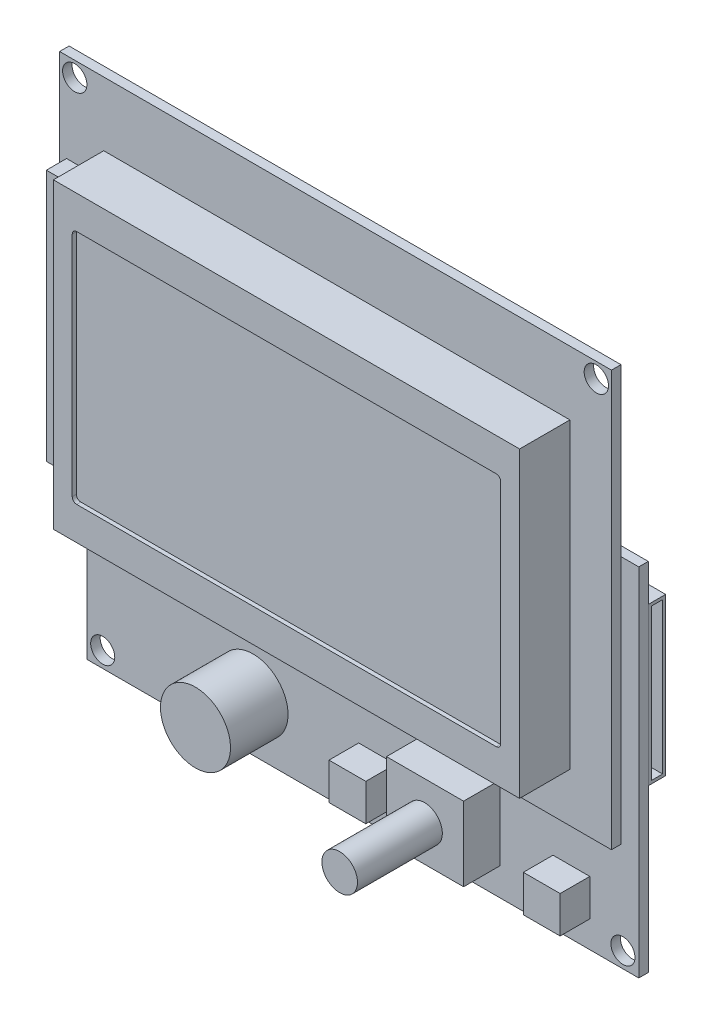
SolidWorks part; units mm, degrees
ref_plane "Front Plane" through (0, 0, 0) normal (0, 0, 1) x (1, 0, 0)
ref_plane "Top Plane" through (0, 0, 0) normal (0, 1, 0) x (1, 0, 0)
ref_plane "Right Plane" through (0, 0, 0) normal (1, 0, 0) x (0, 0, -1)
ref_plane "Plane2" through (0, 0, 4.6) normal (0, 0, -1) x (-1, 0, 0)
sketch "Sketch6" plane through (0, 0, 4.6) normal (0, 0, -1) x (-1, 0, 0)
  line L0 (4.6, 88.466) -> (0.5, 88.466) construction
  line L24 (0, 21.016) -> (93, 21.016)
  line L25 (93, 21.016) -> (93, 91.016)
  line L26 (93, 91.016) -> (0, 91.016)
  line L27 (0, 91.016) -> (0, 21.016)
  line L28 (0, 0) -> (-20.1226, 0) construction
  line L29 (92.5, 88.466) -> (88.4, 88.466) construction
  circle A0 centre (90.45, 88.466) radius 2.05
  circle A1 centre (2.55, 88.466) radius 2.05
extrude "Green PCB" add sketch "Sketch6" against normal blind 1.6 separate body
ref_plane "Plane6" through (0, 0, 1.6) normal (0, 0, 1) x (1, 0, 0)
sketch "Sketch57" plane through (0, 0, 1.6) normal (0, 0, 1) x (1, 0, 0)
  line L0 (-93, 60) -> (-93, 0)
  line L1 (-93, 0) -> (0, 0)
  line L2 (0, 0) -> (0, 60)
  line L3 (0, 60) -> (-93, 60)
  line L4 (0, 0) -> (25.8549, 0) construction
  circle A0 centre (-2.667, 2.667) radius 2.032
  circle A1 centre (-90.333, 2.667) radius 2.032
extrude "White PCB" add sketch "Sketch57" against normal blind 1.6 separate body
sketch "Sketch122" plane through (0, 0, 0) normal (0, 0, 1) x (1, 0, 0)
  line L2 (-84.11, 60) -> (-84.11, 0)
  line L3 (-84.11, 41.966) -> (-84.11, 39.934)
  line L4 (-76.49, 41.966) -> (-76.49, 39.934)
  line L5 (0, 39.68) -> (-93, 39.68)
  line L6 (-76.744, 39.68) -> (-83.856, 39.68)
  line L7 (-76.744, 42.22) -> (-83.856, 42.22)
  line L8 (0, 42.22) -> (-93, 42.22) construction
  line L9 (-84.11, 60) -> (-84.11, 0) construction
  line L10 (0, 39.68) -> (-93, 39.68) construction
  line L11 (-76.49, 60) -> (-76.49, 0) construction
  arc A0 (-83.856, 42.22) -> (-84.11, 41.966) centre (-83.856, 41.966) ccw
  arc A1 (-84.11, 39.934) -> (-83.856, 39.68) centre (-83.856, 39.934) ccw
  arc A2 (-76.744, 39.68) -> (-76.49, 39.934) centre (-76.744, 39.934) ccw
  arc A3 (-76.49, 41.966) -> (-76.744, 42.22) centre (-76.744, 41.966) ccw
  dimension "D3" = 0.254
  dimension "D1" = 8.89
  dimension "D2" = 20.32
extrude "Jumper" add sketch "Sketch122" against normal blind 8.509
sketch "Sketch123" plane through (0, 0, 4.6) normal (0, 0, -1) x (-1, 0, 0)
  line L2 (80.3, 21.016) -> (80.3, 91.016)
  line L3 (80.3, 21.905) -> (80.3, 22.921)
  line L8 (29.718, 23.175) -> (80.046, 23.175)
  line L9 (0, 21.651) -> (93, 21.651)
  line L10 (29.718, 21.651) -> (80.046, 21.651)
  line L12 (0, 23.175) -> (93, 23.175) construction
  line L13 (29.464, 91.016) -> (29.464, 21.016)
  line L14 (29.464, 22.921) -> (29.464, 21.905)
  line L15 (0, 21.651) -> (93, 21.651) construction
  arc A0 (29.718, 23.175) -> (29.464, 22.921) centre (29.718, 22.921) ccw
  arc A1 (29.464, 21.905) -> (29.718, 21.651) centre (29.718, 21.905) ccw
  arc A2 (80.046, 23.175) -> (80.3, 22.921) centre (80.046, 22.921) cw
  arc A3 (80.3, 21.905) -> (80.046, 21.651) centre (80.046, 21.905) cw
  dimension "D4" = 0.254
  dimension "D1" = 12.7
  dimension "D2" = 0.635
  dimension "D3" = 29.464
extrude "LCD Pins" add sketch "Sketch123" along normal up to surface (3 mm away) up to face at (-88.301, 2.667, 1.6)
ref_plane "Plane8" through (0, 0, 6.2) normal (0, 0, 1) x (1, 0, 0)
sketch "Sketch98" plane through (0, 0, 6.2) normal (0, 0, 1) x (1, 0, 0)
  line L0 (-85.56, 75.98) -> (-91.83, 75.98)
  line L1 (-91.83, 75.98) -> (-91.83, 33.48)
  line L2 (-91.83, 33.48) -> (-85.56, 33.48)
  line L3 (-85.56, 33.48) -> (-85.56, 29.25)
  line L4 (-85.56, 29.25) -> (-7, 29.25)
  line L5 (-7, 29.25) -> (-7, 80.25)
  line L6 (-7, 80.25) -> (-85.56, 80.25)
  line L7 (-85.56, 80.25) -> (-85.56, 75.98)
extrude "LCD Base" add sketch "Sketch98" along normal blind 3.4
ref_plane "Plane9" through (0, 0, 9.5999) normal (0, 0, 1) x (1, 0, 0)
sketch "Sketch109" plane through (0, 0, 9.5999) normal (0, 0, 1) x (1, 0, 0)
  line L0 (-85.56, 29.25) -> (-85.56, 80.25)
  line L1 (-85.56, 29.25) -> (-7, 29.25)
  line L2 (-7, 29.25) -> (-7, 80.25)
  line L3 (-85.56, 80.25) -> (-7, 80.25)
extrude "LCD Screen" add sketch "Sketch109" along normal blind 5.0836
ref_plane "Plane10" through (0, 0, 14.7521) normal (0, 0, 1) x (1, 0, 0)
sketch "Sketch121" plane through (0, 0, 14.7521) normal (0, 0, 1) x (1, 0, 0)
  line L0 (-82.385, 73.9) -> (-82.385, 35.6)
  line L1 (-10.175, 35.6) -> (-10.175, 73.9)
  line L2 (-81.623, 74.662) -> (-10.937, 74.662)
  line L3 (-81.623, 34.838) -> (-10.937, 34.838)
  arc A0 (-82.385, 35.6) -> (-81.623, 34.838) centre (-81.623, 35.6) ccw
  arc A1 (-10.937, 34.838) -> (-10.175, 35.6) centre (-10.937, 35.6) ccw
  arc A2 (-10.175, 73.9) -> (-10.937, 74.662) centre (-10.937, 73.9) ccw
  arc A3 (-81.623, 74.662) -> (-82.385, 73.9) centre (-81.623, 73.9) ccw
extrude "LCD Glass" cut sketch "Sketch121" against normal blind 0.762
ref_plane "Plane4" through (0, 0, -2.93) normal (0, 0, -1) x (-1, 0, 0)
sketch "Sketch17" plane through (0, 0, -2.93) normal (0, 0, -1) x (-1, 0, 0)
  line L0 (25.5, 53.721) -> (0, 53.721)
  line L1 (0, 53.721) -> (0, 27.2542)
  line L2 (0, 27.2542) -> (25.5, 27.2542)
  line L3 (25.5, 27.2542) -> (25.5, 53.721)
  line L6 (93, 0) -> (0, 0) construction
  dimension "D1" = 53.721
extrude "SD Card" add sketch "Sketch17" against normal blind 2.93 separate body
ref_plane "Plane5" through (0, 0, 1.6) normal (0, 0, -1) x (-1, 0, 0)
sketch "Sketch24" plane through (0, 0, 1.6) normal (0, 0, -1) x (-1, 0, 0)
  line L0 (47.2, 10.7) -> (41, 10.7)
  line L1 (41, 10.7) -> (41, 4.5)
  line L2 (41, 4.5) -> (47.2, 4.5)
  line L3 (47.2, 4.5) -> (47.2, 10.7)
extrude "Stop" add sketch "Sketch24" against normal blind 5 separate body
sketch "Sketch32" plane through (0, 0, 1.6) normal (0, 0, -1) x (-1, 0, 0)
  line L0 (14.45, 10.7) -> (8.25, 10.7)
  line L1 (8.25, 10.7) -> (8.25, 4.5)
  line L2 (8.25, 4.5) -> (14.45, 4.5)
  line L3 (14.45, 4.5) -> (14.45, 10.7)
extrude "Light" add sketch "Sketch32" against normal blind 5 separate body
sketch "Sketch40" plane through (0, 0, 1.6) normal (0, 0, -1) x (-1, 0, 0)
  line L0 (36.42, 17.15) -> (23.42, 17.15)
  line L1 (23.42, 17.15) -> (23.42, 4.65)
  line L2 (23.42, 4.65) -> (36.42, 4.65)
  line L3 (36.42, 4.65) -> (36.42, 17.15)
extrude "Selector" add sketch "Sketch40" against normal blind 6.1 separate body
sketch "Sketch41" plane through (0, 0, 7.7) normal (0, 0, 1) x (1, 0, 0)
  line L36 (-33, 10.65) -> (-30, 10.65) construction
  circle A0 centre (-30, 10.65) radius 3
extrude "Selector Shaft" add sketch "Sketch41" along normal blind 14.3
sketch "Sketch49" plane through (0, 0, 1.6) normal (0, 0, -1) x (-1, 0, 0)
  line L36 (70.9, 8.9) -> (65, 8.9) construction
  circle A0 centre (65, 8.9) radius 5.9
extrude "Speaker" add sketch "Sketch49" against normal blind 9.7 separate body
ref_plane "Plane7" through (0, 0, 0) normal (0, 0, -1) x (-1, 0, 0)
sketch "Sketch77" plane through (0, 0, 0) normal (0, 0, -1) x (-1, 0, 0)
  line L16 (64.1, 33.15) -> (64.1, 30) construction
  circle A0 centre (64.1, 30) radius 3.15
extrude "Capacitor" add sketch "Sketch77" along normal blind 8
sketch "Sketch78" plane through (0, 0, 0) normal (0, 0, -1) x (-1, 0, 0)
  line L0 (86.4, 58.3) -> (86.4, 49.7)
  line L1 (86.4, 49.7) -> (66.15, 49.7)
  line L2 (66.15, 49.7) -> (66.15, 58.3)
  line L3 (66.15, 58.3) -> (86.4, 58.3)
extrude "EPX1" add sketch "Sketch78" along normal blind 8.7 separate body
sketch "Sketch88" plane through (0, 0, 0) normal (0, 0, -1) x (-1, 0, 0)
  line L0 (65.1, 58.3) -> (65.1, 49.7)
  line L1 (65.1, 49.7) -> (44.85, 49.7)
  line L2 (44.85, 49.7) -> (44.85, 58.3)
  line L3 (44.85, 58.3) -> (65.1, 58.3)
extrude "Exp2" add sketch "Sketch88" along normal blind 8.7 separate body
shell "Shell2" thickness 0.508
shell "Shell3" thickness 1.016
shell "Shell4" thickness 1.016
